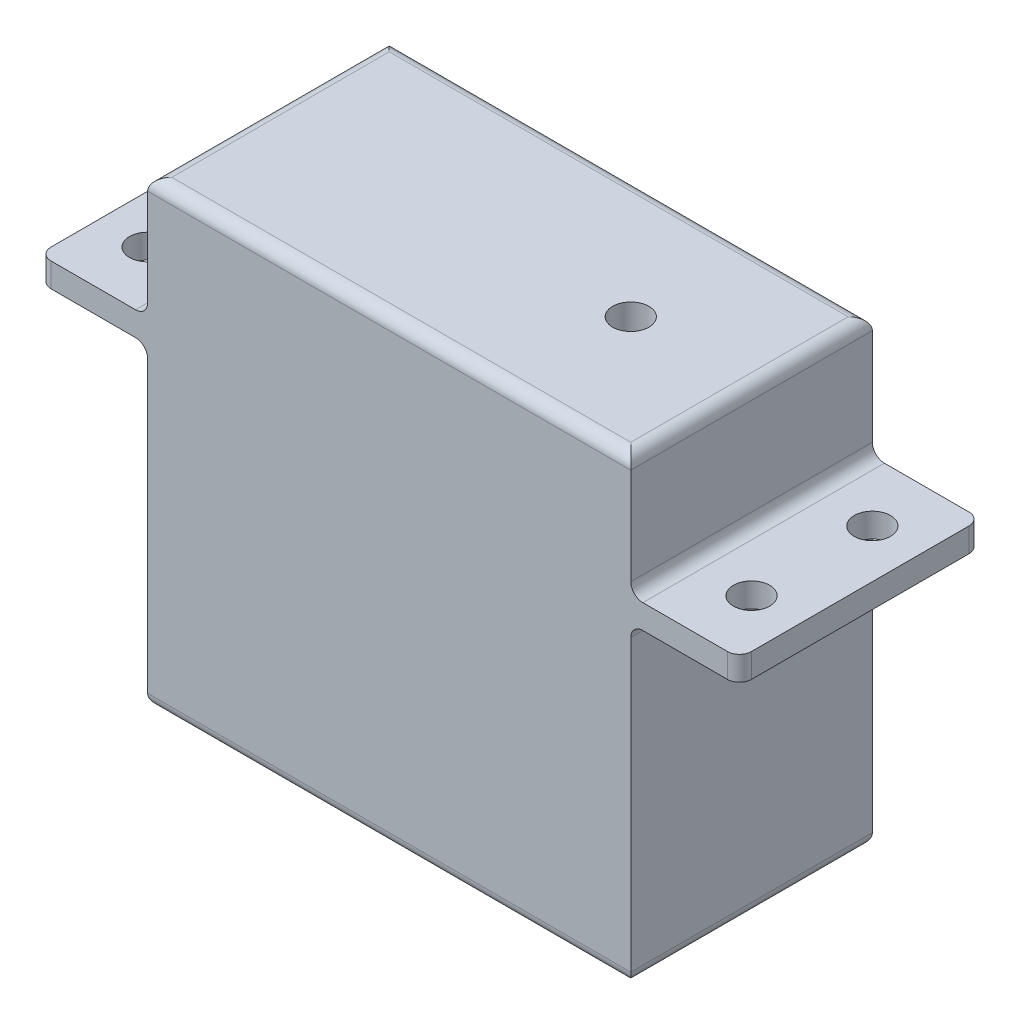
SolidWorks part; units mm, degrees
ref_plane "Front Plane" through (0, 0, 0) normal (0, 0, 1) x (1, 0, 0)
ref_plane "Top Plane" through (0, 0, 0) normal (0, 1, 0) x (1, 0, 0)
ref_plane "Right Plane" through (0, 0, 0) normal (1, 0, 0) x (0, 0, -1)
sketch "Sketch1" plane through (0, 0, 0) normal (0, 1, 0) x (1, 0, 0)
  line L1 (-22.6316, 6.3158) -> (17.3684, 6.3158)
  line L2 (-22.6316, 6.3158) -> (-22.6316, -13.6842)
  line L3 (-22.6316, -13.6842) -> (17.3684, -13.6842)
  line L4 (17.3684, 6.3158) -> (17.3684, -13.6842)
  circle A0 centre (7.3684, -3.6842) radius 1.5 construction
  dimension "D1" = 40
  dimension "D2" = 20
extrude "Boss-Extrude1" add sketch "Sketch1" along normal blind 38
sketch "Sketch2" plane through (0, 38, 0) normal (0, 1, 0) x (1, 0, 0)
  line L1 (17.3684, 6.3158) -> (7.3684, 6.3158)
  line L2 (17.3684, 6.3158) -> (17.3684, -3.6842)
  line L3 (17.3684, -3.6842) -> (7.3684, -3.6842)
  line L4 (7.3684, 6.3158) -> (7.3684, -3.6842)
  circle A0 centre (7.3684, -3.6842) radius 2.5
  circle A1 centre (7.3684, -3.6842) radius 1.5
  dimension "D3" = 5
  dimension "D4" = 3
  dimension "D1" = 10
  dimension "D2" = 10
extrude "Cut-Extrude1" cut sketch "Sketch2" against normal blind 10 contours A1
sketch "Sketch3" plane through (17.3684, 0, 0) normal (1, 0, 0) x (0, 0, -1)
  line L0 (-13.6842, 0) -> (-13.6842, 26)
  line L1 (-13.6842, 38) -> (-13.6842, 0) construction
  line L2 (6.3158, 38) -> (6.3158, 0) construction
  line L3 (-13.6842, 26) -> (6.3158, 26)
  line L4 (-13.6842, 26) -> (-13.6842, 28)
  line L5 (-13.6842, 28) -> (6.3158, 28)
  line L6 (6.3158, 26) -> (6.3158, 28)
  line L7 (-13.6842, 38) -> (-13.6842, 0) construction
  line L8 (-2.1842, 38) -> (-5.1842, 38) construction
  line M7 (6.3158, 0) -> (6.3158, 38)
  line M9 (-13.6842, 38) -> (-13.6842, 0)
  dimension "D1" = 26
  dimension "D2" = 2
extrude "Boss-Extrude2" add sketch "Sketch3" along normal blind 9 contours L5 L3 M9 M7
sketch "Sketch4" plane through (0, 0, 13.6842) normal (0, 0, 1) x (1, 0, 0)
sketch "Sketch6" plane through (0, 28, 0) normal (0, 1, 0) x (1, 0, 0)
  line L0 (26.3684, -13.6842) -> (26.3684, 6.3158) construction
  line L3 (17.3684, -3.6842) -> (26.3684, -3.6842) construction
  line L4 (17.3684, -13.6842) -> (17.3684, 6.3158) construction
  circle A0 centre (22.3684, 1.3158) radius 1.5
  circle A1 centre (22.3684, -8.6842) radius 1.5
  dimension "D5" = 3
  dimension "D6" = 3
  dimension "D1" = 4
  dimension "D2" = 5
  dimension "D3" = 4
  dimension "D4" = 5
extrude "Cut-Extrude2" cut sketch "Sketch6" against normal through all
sketch "Sketch7" plane through (-22.6316, 0, 0) normal (-1, 0, 0) x (0, 0, 1)
  line L0 (-6.3158, 0) -> (-6.3158, 26)
  line L1 (-6.3158, 38) -> (-6.3158, 0) construction
  line L2 (13.6842, 38) -> (13.6842, 0) construction
  line L3 (-6.3158, 26) -> (13.6842, 26)
  line L4 (-6.3158, 26) -> (-6.3158, 28)
  line L5 (-6.3158, 28) -> (13.6842, 28)
  line L6 (13.6842, 26) -> (13.6842, 28)
  line M4 (13.6842, 0) -> (13.6842, 38)
  line M6 (-6.3158, 38) -> (-6.3158, 0)
  dimension "D1" = 26
  dimension "D2" = 2
extrude "Boss-Extrude5" add sketch "Sketch7" along normal blind 9 contours L5 L3 M6 M4
sketch "Sketch8" plane through (0, 28, 0) normal (0, 1, 0) x (1, 0, 0)
  line L0 (-31.6316, 6.3158) -> (-31.6316, -13.6842) construction
  line L2 (-22.6316, -3.6842) -> (-31.6316, -3.6842) construction
  line L3 (-22.6316, 6.3158) -> (-22.6316, -13.6842) construction
  circle A0 centre (-27.6316, 1.3158) radius 1.5047
  circle A1 centre (-27.6316, -8.6842) radius 1.5047
  dimension "D1" = 3.0094
  dimension "D2" = 4
  dimension "D3" = 5
  dimension "D4" = 5
extrude "Cut-Extrude3" cut sketch "Sketch8" against normal through all
fillet "Fillet1" radius 1 16 edges at (-22.6316, 26, 3.6842) (17.3684, 26, 3.6842) (17.3684, 28, 3.6842) (-22.6316, 28, 3.6842) (-22.6316, 0, 3.6842) (-2.6316, 0, -6.3158) (-2.6316, 0, 13.6842) (17.3684, 0, 3.6842) (17.3684, 38, 3.6842) (-22.6316, 38, 3.6842) (-2.6316, 38, -6.3158) (-2.6316, 38, 13.6842) (-31.6316, 27, -6.3158) (-31.6316, 27, 13.6842) (26.3684, 27, 13.6842) (26.3684, 27, -6.3158)
sketch "Sketch9" plane through (0, 38, 0) normal (0, 1, 0) x (1, 0, 0)
  line L0 (-27.6316, 1.3158) -> (22.3684, 1.3158)
  line L1 (22.3684, 1.3158) -> (22.3684, -8.6842)
  line L2 (22.3684, -8.6842) -> (-27.6316, -8.6842)
  line L3 (-27.6316, -8.6842) -> (-27.6316, 1.3158)
  dimension "D1" = 50
  dimension "D2" = 10
